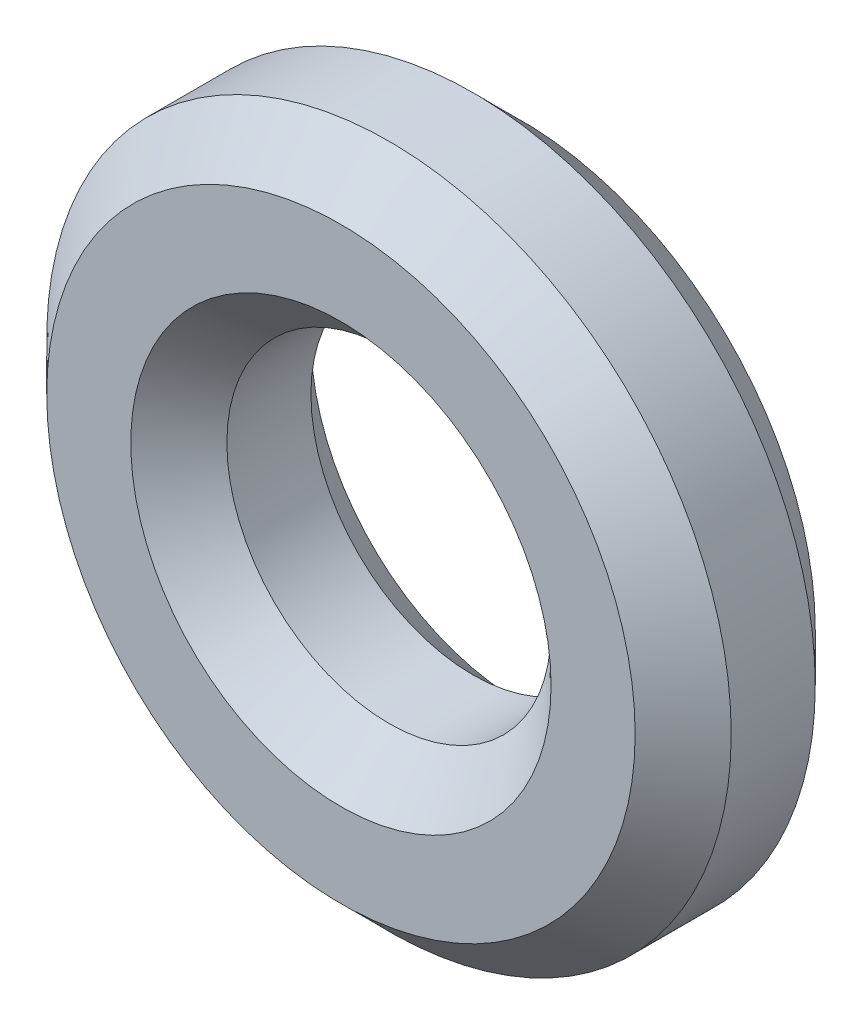
SolidWorks part; units mm, degrees
ref_plane "Plano frontal" through (0, 0, 0) normal (0, 0, 1) x (1, 0, 0)
ref_plane "Plano superior" through (0, 0, 0) normal (0, 1, 0) x (1, 0, 0)
ref_plane "Plano direito" through (0, 0, 0) normal (1, 0, 0) x (0, 0, -1)
sketch "Esboço1" plane through (0, 0, 0) normal (0, 0, 1) x (1, 0, 0)
  circle A0 centre (0, 0) radius 5.7
  circle A1 centre (0, 0) radius 2.7
  dimension "D1" = 5.4
  dimension "D2" = 3
extrude "Ressalto-extrusão1" add sketch "Esboço1" along normal blind 3
chamfer "Chanfro1" distance 0.8 angle 45 4 edges at (2.7, 0, 0) (5.7, 0, 0) (2.7, 0, 3) (5.7, 0, 3)
